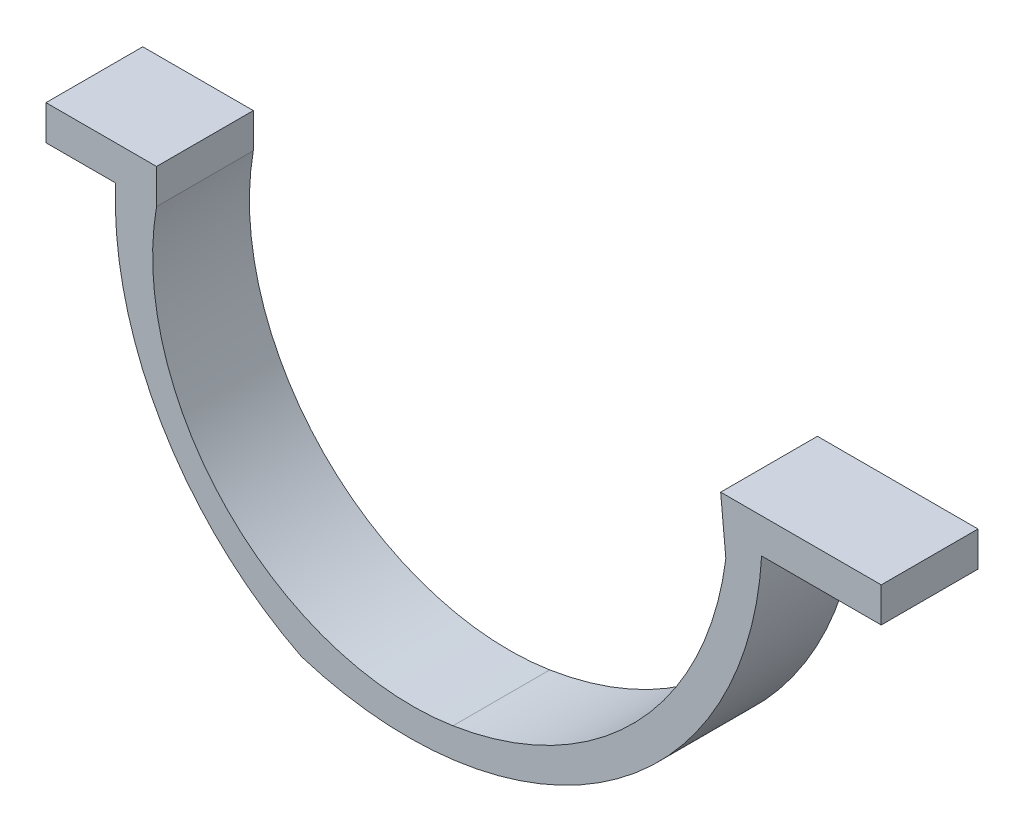
SolidWorks part; units mm, degrees
ref_plane "정면" through (0, 0, 0) normal (0, 0, 1) x (1, 0, 0)
ref_plane "윗면" through (0, 0, 0) normal (0, 1, 0) x (1, 0, 0)
ref_plane "우측면" through (0, 0, 0) normal (1, 0, 0) x (0, 0, -1)
sketch "스케치1" plane through (0, 0, 0) normal (0, 0, 1) x (1, 0, 0)
  line L0 (0, 0) -> (12.3567, 0)
  line L1 (12.3567, 0) -> (12.3567, 3.5952)
  line L2 (12.3567, 3.5952) -> (-4.234, 3.5952)
  line L3 (-62.5237, 0) -> (-62.5237, 3.5952)
  line L4 (-62.5237, 3.5952) -> (-73.9448, 3.5952)
  line L5 (-73.9448, 3.5952) -> (-73.9448, 0)
  line L6 (-73.9448, 0) -> (-66.7533, 0)
  line L7 (-4.234, 3.5952) -> (-3.6986, -2.0845)
  arc A0 (0, 0) -> (-47.5638, -32.7781) centre (-36.5487, 2.1366) cw
  arc A1 (-3.6986, -2.0845) -> (-31.8928, -31.1418) centre (-37.1766, 2.1921) cw
  arc A2 (-31.8928, -31.1418) -> (-62.5237, 0) centre (-36.0938, -4.6388) cw
  arc A3 (-47.5638, -32.7781) -> (-66.7533, 0) centre (-31.7468, -1.5121) cw
extrude "보스-돌출1" add sketch "스케치1" along normal mid plane 10
